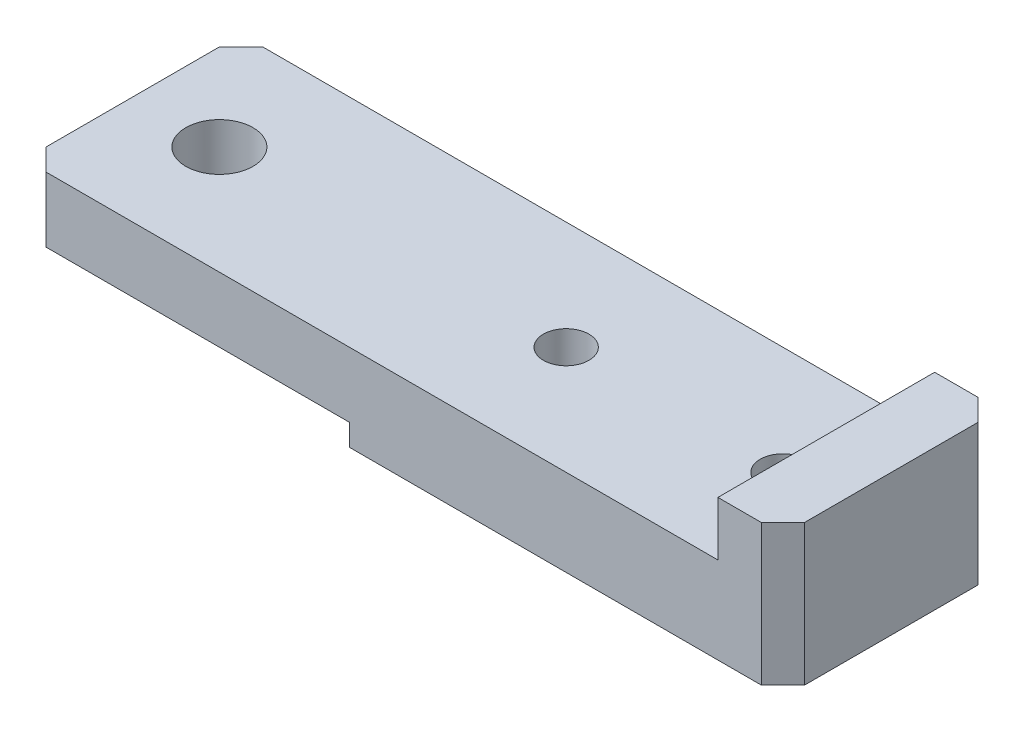
SolidWorks part; units mm, degrees
ref_plane "前视基准面" through (0, 0, 0) normal (0, 0, 1) x (1, 0, 0)
ref_plane "上视基准面" through (0, 0, 0) normal (0, 1, 0) x (1, 0, 0)
ref_plane "右视基准面" through (0, 0, 0) normal (1, 0, 0) x (0, 0, -1)
other "Configuration Table"
sketch "草图1" plane through (0, 0, 0) normal (0, 0, 1) x (1, 0, 0)
  line L0 (0, 4) -> (0, 10)
  line L1 (0, 10) -> (64, 10)
  line L2 (70, 10) -> (70, 2)
  line L3 (70, 2) -> (30, 2)
  line L4 (0, 4) -> (30, 4)
  line L5 (30, 4) -> (30, 2)
  line L6 (0, 4) -> (0, 0) construction
  line L7 (70, 10) -> (70, 15)
  line L8 (70, 15) -> (64, 15)
  line L9 (64, 15) -> (64, 10)
  dimension "D1" = 8
  dimension "D2" = 10
  dimension "D3" = 70
  dimension "D4" = 6
  dimension "D5" = 30
  dimension "D6" = 5
  dimension "D7" = 6
extrude "凸台-拉伸1" add sketch "草图1" along normal mid plane 20
sketch "草图3" plane through (0, 4, 0) normal (0, -1, 0) x (1, 0, 0)
  circle A0 centre (8, 0) radius 5
  dimension "D1" = 10
  dimension "D2" = 8
extrude "凸台-拉伸2" add sketch "草图3" along normal blind 2
chamfer "倒角1" distance 2 angle 45 2 edges at (0, 7, -10) (0, 7, 10)
chamfer "倒角2" distance 2 angle 45 2 edges at (70, 8.5, -10) (70, 8.5, 10)
sketch "草图4" plane through (0, 2, 0) normal (0, -1, 0) x (1, 0, 0)
  line L0 (70, 8) -> (70, -8) construction
  circle A0 centre (40, 0) radius 2.1
  circle A1 centre (60, 0) radius 2.1
  circle A2 centre (8, 0) radius 3.1
  dimension "D2" = 6.2
  dimension "D3" = 4.2
  dimension "D4" = 4.2
  dimension "D1" = 20
  dimension "D5" = 10
extrude "切除-拉伸1" cut sketch "草图4" against normal through all
fillet "圆角1" radius 1 1 edges at (8, 4, 5)
